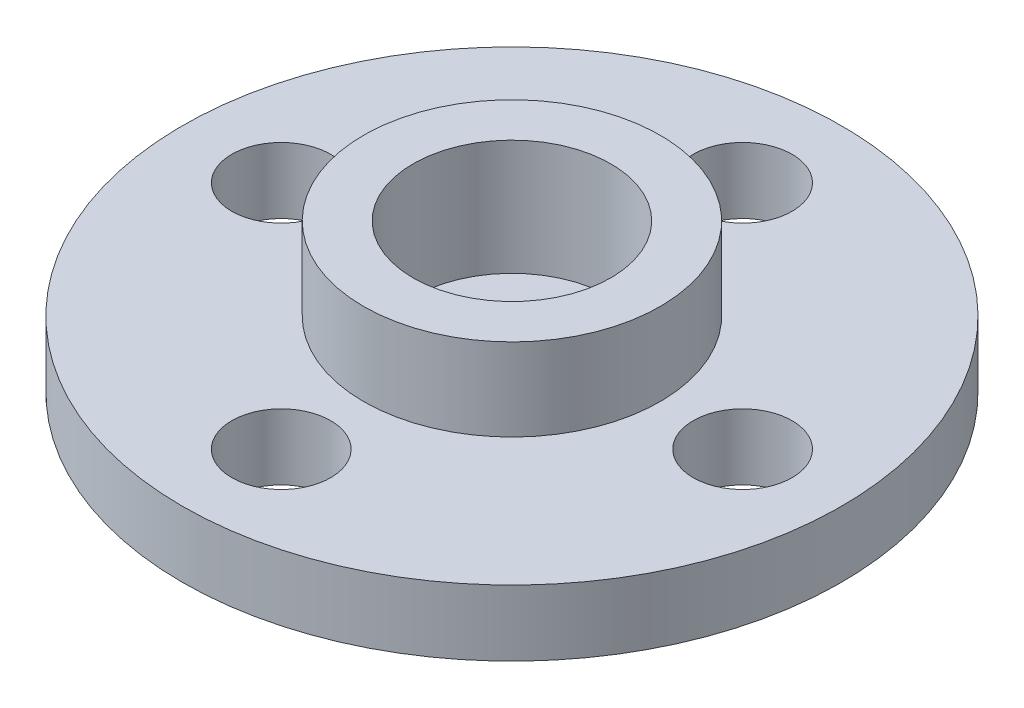
SolidWorks part; units mm, degrees
ref_plane "前视基准面" through (0, 0, 0) normal (0, 0, 1) x (1, 0, 0)
ref_plane "上视基准面" through (0, 0, 0) normal (0, 1, 0) x (1, 0, 0)
ref_plane "右视基准面" through (0, 0, 0) normal (1, 0, 0) x (0, 0, -1)
other "Configuration Table"
sketch "草图1" plane through (0, 0, 0) normal (0, 1, 0) x (1, 0, 0)
  circle A0 centre (0, 0) radius 10
  circle A1 centre (0, 0) radius 7 construction
  circle A2 centre (0, 7) radius 1.5
  circle A3 centre (0, 0) radius 1.5
  circle A4 centre (7, 0) radius 1.5
  circle A5 centre (0, -7) radius 1.5
  circle A6 centre (-7, 0) radius 1.5
  point P16 (0, 0)
  dimension "D1" = 20
  dimension "D2" = 14
  dimension "D3" = 3
  dimension "D5" = 3
  dimension "D4" = 4
extrude "凸台-拉伸1" add sketch "草图1" along normal blind 2
sketch "草图2" plane through (0, 2, 0) normal (0, 1, 0) x (1, 0, 0)
  circle A0 centre (0, 0) radius 3
  dimension "D1" = 6
extrude "切除-拉伸1" cut sketch "草图2" against normal blind 1
sketch "草图3" plane through (0, 2, 0) normal (0, 1, 0) x (1, 0, 0)
  circle A0 centre (0, 0) radius 3 construction
  circle A1 centre (0, 0) radius 3
  circle A2 centre (0, 0) radius 4.5
  dimension "D1" = 9
extrude "凸台-拉伸2" add sketch "草图3" along normal blind 2.5
